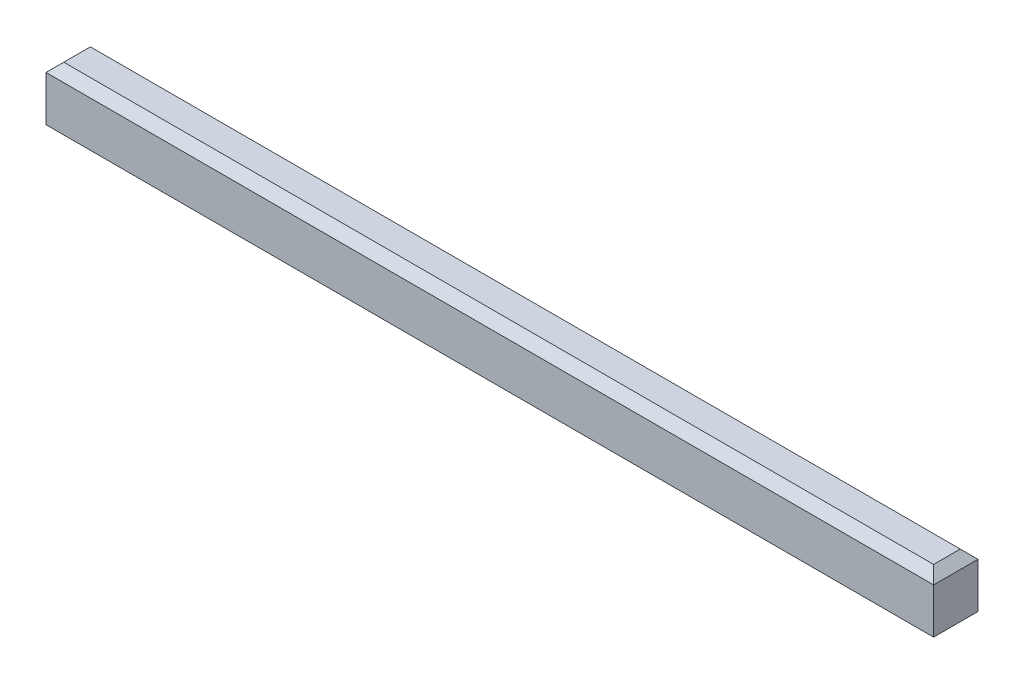
SolidWorks part; units mm, degrees
ref_plane "정면" through (0, 0, 0) normal (0, 0, 1) x (1, 0, 0)
ref_plane "윗면" through (0, 0, 0) normal (0, 1, 0) x (1, 0, 0)
ref_plane "우측면" through (0, 0, 0) normal (1, 0, 0) x (0, 0, -1)
sketch "스케치1" plane through (0, 0, 0) normal (0, 0, 1) x (1, 0, 0)
  line L1 (0, 0) -> (100, 0)
  line L2 (0, 0) -> (0, 6.1)
  line L3 (0, 6.1) -> (100, 6.1)
  line L4 (100, 0) -> (100, 6.1)
  dimension "D1" = 100
  dimension "D2" = 6.1
extrude "보스-돌출1" add sketch "스케치1" along normal mid plane 5
chamfer "모따기1" distance 1 angle 45 4 edges at (100, 6.1, 0) (50, 6.1, 2.5) (0, 6.1, 0) (50, 6.1, -2.5)
